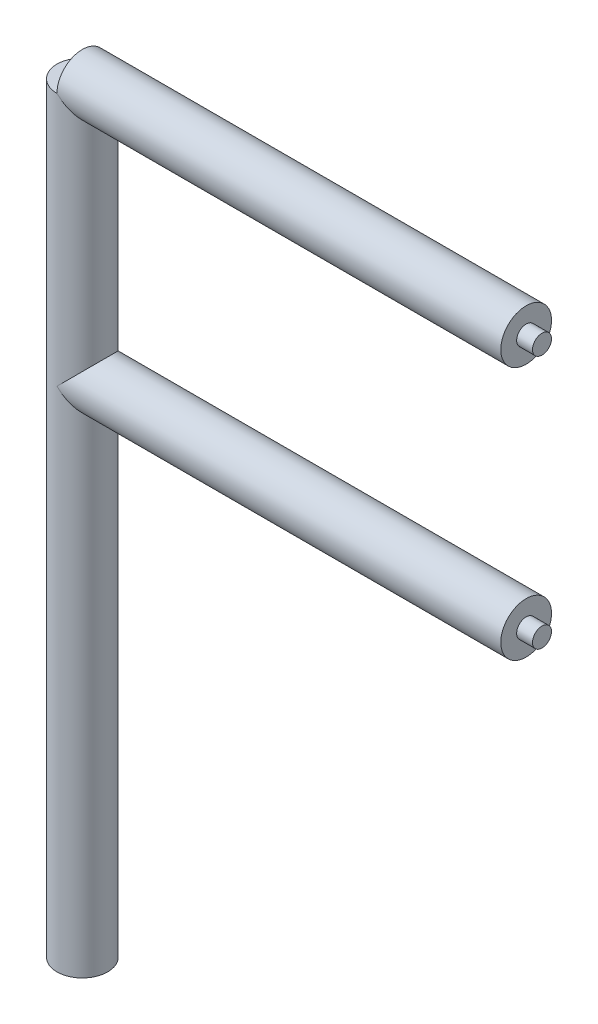
SolidWorks part; units mm, degrees
ref_plane "Front Plane" through (0, 0, 0) normal (0, 0, 1) x (1, 0, 0)
ref_plane "Top Plane" through (0, 0, 0) normal (0, 1, 0) x (1, 0, 0)
ref_plane "Right Plane" through (0, 0, 0) normal (1, 0, 0) x (0, 0, -1)
sketch "Sketch1" plane through (0, 0, 0) normal (0, 1, 0) x (1, 0, 0)
  circle A0 centre (0, 0) radius 4
extrude "Boss-Extrude1" add sketch "Sketch1" against normal blind 80
sketch "Sketch3" plane through (0, 0, 0) normal (1, 0, 0) x (0, 0, -1)
  circle A0 centre (0, 0) radius 4
extrude "Boss-Extrude3" add sketch "Sketch3" along normal blind 70
sketch "Sketch4" plane through (0, 0, 0) normal (0, 1, 0) x (1, 0, 0)
  circle A0 centre (0, 0) radius 4
extrude "Boss-Extrude4" add sketch "Sketch4" along normal blind 40
sketch "Sketch5" plane through (0, 0, 0) normal (1, 0, 0) x (0, 0, -1)
  line L0 (4, 40) -> (-4, 40) construction
  circle A0 centre (0, 40) radius 4
extrude "Boss-Extrude5" add sketch "Sketch5" along normal blind 70
sketch "Sketch7" plane through (70, 0, 0) normal (1, 0, 0) x (0, 0, -1)
  circle A0 centre (0, 40) radius 1.5
  circle A1 centre (0, 0) radius 1.5
  dimension "D1" = 3
extrude "Boss-Extrude6" add sketch "Sketch7" along normal blind 2.5
